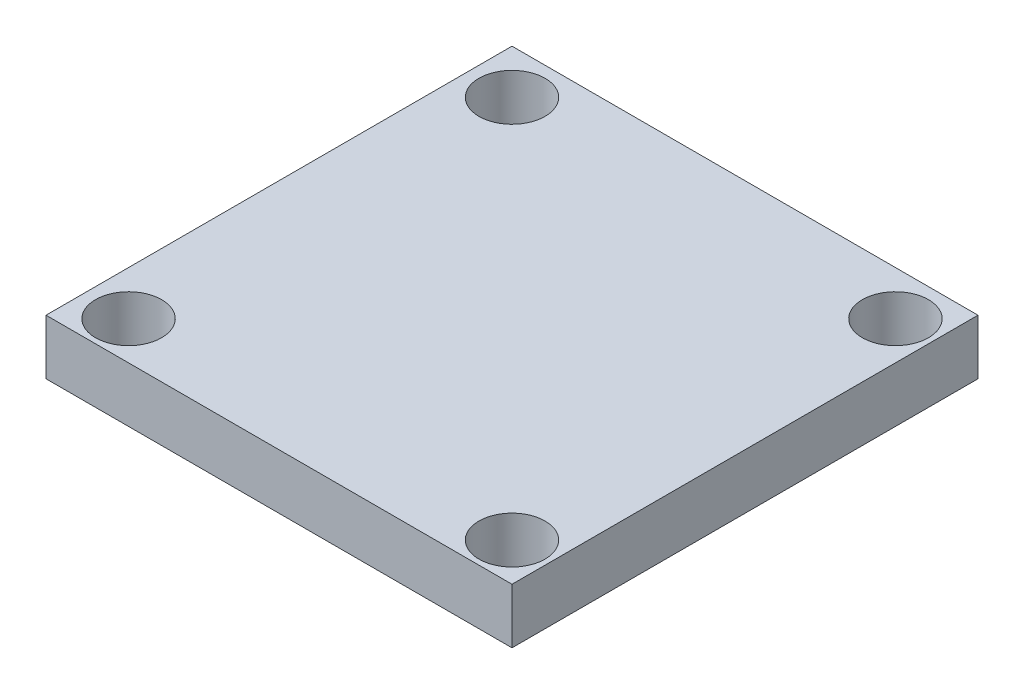
SolidWorks part; units mm, degrees
ref_plane "Front Plane" through (0, 0, 0) normal (0, 0, 1) x (1, 0, 0)
ref_plane "Top Plane" through (0, 0, 0) normal (0, 1, 0) x (1, 0, 0)
ref_plane "Right Plane" through (0, 0, 0) normal (1, 0, 0) x (0, 0, -1)
sketch "Sketch1" plane through (0, 0, 0) normal (0, 1, 0) x (1, 0, 0)
  line L1 (-21.15, -21.15) -> (21.15, -21.15)
  line L2 (-21.15, -21.15) -> (-21.15, 21.15)
  line L3 (-21.15, 21.15) -> (21.15, 21.15)
  line L4 (21.15, -21.15) -> (21.15, 21.15)
  line L5 (-21.15, -21.15) -> (21.15, 21.15) construction
  line L6 (-21.15, 21.15) -> (21.15, -21.15) construction
  point P0 (0, 0)
  dimension "D1" = 42.3
  dimension "D2" = 42.3
extrude "Boss-Extrude2" add sketch "Sketch1" along normal blind 5
sketch "Sketch2" plane through (0, 5, 0) normal (0, 1, 0) x (1, 0, 0)
  line L0 (-21.15, 21.15) -> (0, 0)
  circle A0 centre (-17.1274, 17.1274) radius 3
extrude "Cut-Extrude1" cut sketch "Sketch2" against normal blind 5 contours A0
pattern_circular "CirPattern1" count 4 over 360 about axis through (0.275, 0, 0.275) along (0, 1, 0) of "Cut-Extrude1"
